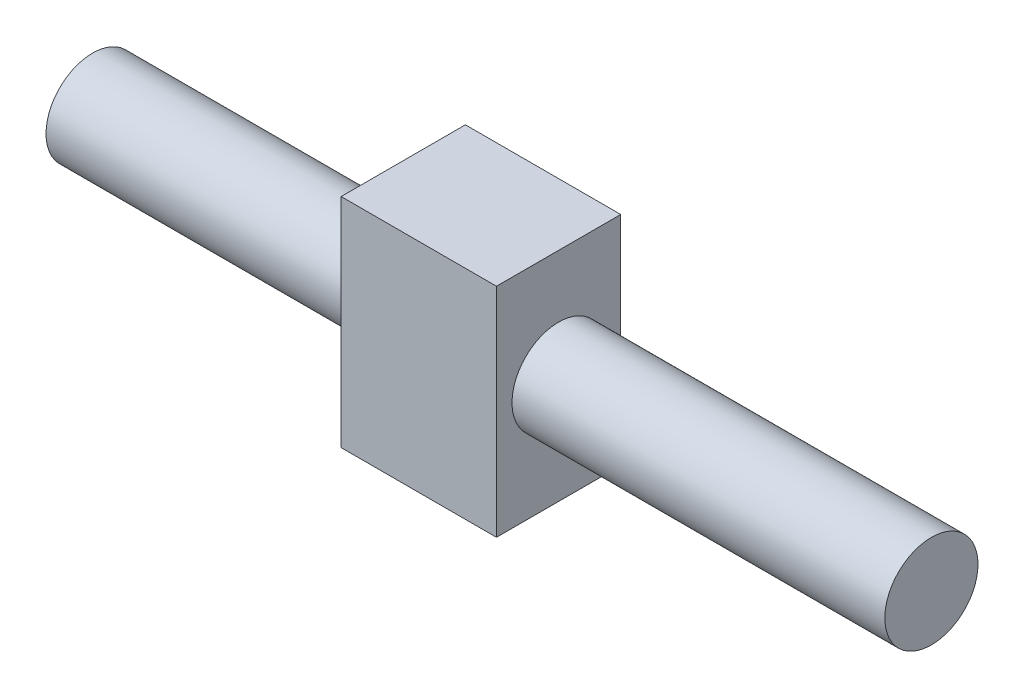
SolidWorks part; units mm, degrees
material "Maple"
ref_plane "Front Plane" through (0, 0, 0) normal (0, 0, 1) x (1, 0, 0)
ref_plane "Top Plane" through (0, 0, 0) normal (0, 1, 0) x (1, 0, 0)
ref_plane "Right Plane" through (0, 0, 0) normal (1, 0, 0) x (0, 0, -1)
sketch "Sketch1" plane through (0, 0, 0) normal (0, 0, 1) x (1, 0, 0)
  line L1 (0, 0) -> (-50, 0)
  line L2 (0, 0) -> (0, 70)
  line L3 (0, 70) -> (-50, 70)
  line L4 (-50, 0) -> (-50, 70)
  dimension "D1" = 70
  dimension "D2" = 50
extrude "Boss-Extrude1" add sketch "Sketch1" along normal blind 40
sketch "Sketch3" plane through (-50, 0, 0) normal (-1, 0, 0) x (0, 0, 1)
  line L0 (40, 70) -> (0, 70) construction
  line L1 (40, 70) -> (40, 0) construction
  circle A0 centre (20, 35) radius 15
  dimension "D1" = 30
  dimension "D2" = 35
  dimension "D3" = 20
extrude "Boss-Extrude3" add sketch "Sketch3" along normal blind 100
sketch "Sketch4" plane through (0, 0, 0) normal (1, 0, 0) x (0, 0, -1)
  line L0 (-40, 0) -> (-40, 70) construction
  line L1 (-40, 0) -> (0, 0) construction
  circle A0 centre (-20, 35) radius 15
  dimension "D1" = 30
  dimension "D3" = 35
  dimension "D2" = 20
extrude "Boss-Extrude4" add sketch "Sketch4" along normal blind 120
